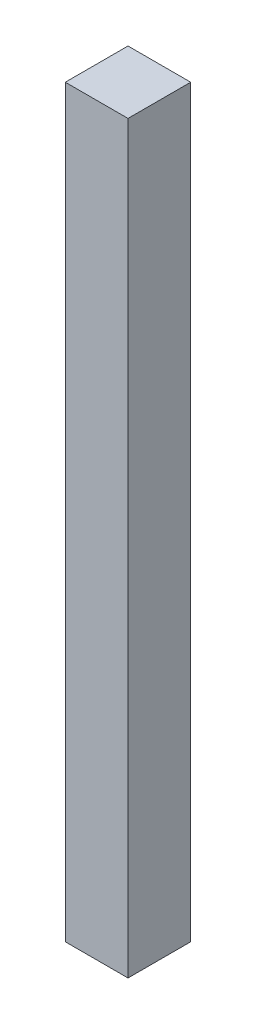
SolidWorks part; units mm, degrees
ref_plane "Plan de face" through (0, 0, 0) normal (0, 0, 1) x (1, 0, 0)
ref_plane "Plan de dessus" through (0, 0, 0) normal (0, 1, 0) x (1, 0, 0)
ref_plane "Plan de droite" through (0, 0, 0) normal (1, 0, 0) x (0, 0, -1)
sketch "Esquisse1" plane through (0, 0, 0) normal (0, 1, 0) x (1, 0, 0)
  line L1 (0, 0) -> (20.3, 0)
  line L2 (0, 0) -> (0, 20.3)
  line L3 (0, 20.3) -> (20.3, 20.3)
  line L4 (20.3, 0) -> (20.3, 20.3)
  dimension "D1" = 20.3
extrude "Boss.-Extru.1" add sketch "Esquisse1" along normal blind 241
